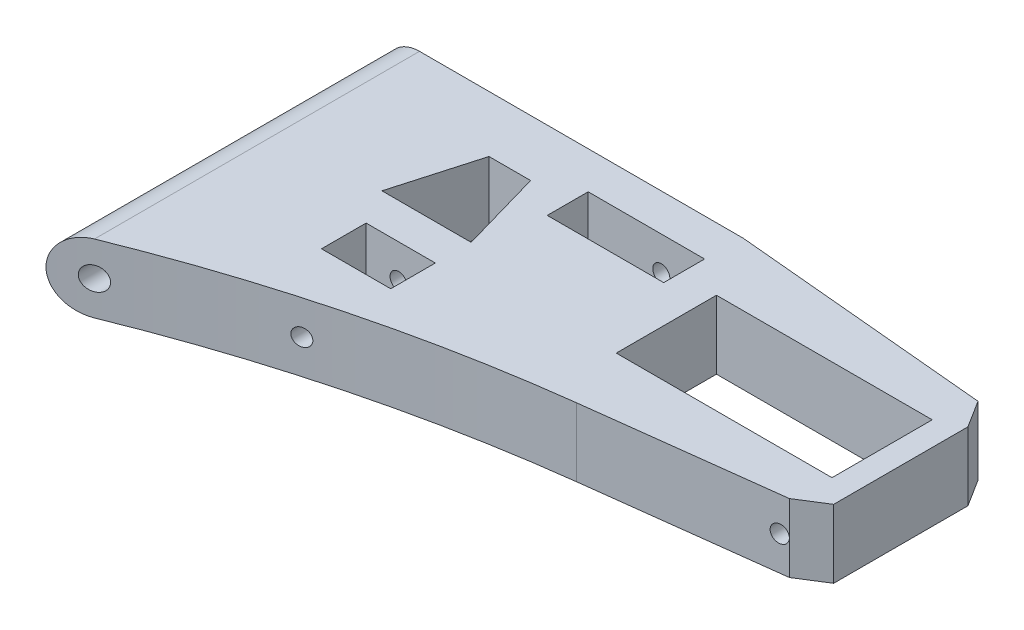
SolidWorks part; units mm, degrees
ref_plane "Front Plane" through (0, 0, 0) normal (0, 0, 1) x (1, 0, 0)
ref_plane "Top Plane" through (0, 0, 0) normal (0, 1, 0) x (1, 0, 0)
ref_plane "Right Plane" through (0, 0, 0) normal (1, 0, 0) x (0, 0, -1)
sketch "Sketch1" plane through (0, 0, 0) normal (0, 1, 0) x (1, 0, 0)
  line L0 (0, 58.1849) -> (0, -59.0181) construction
  line L1 (-25.4, 37.2319) -> (-67.6656, 37.2319)
  line L2 (-67.6656, 37.2319) -> (-86.5378, 37.2319)
  line L3 (-86.5378, 37.2319) -> (-130.7049, 33.1679)
  line L4 (-130.7049, 33.1679) -> (-133.6294, 28.5232)
  line L5 (-133.6294, 28.5232) -> (-133.6294, 5.587)
  line L6 (-133.6294, 5.587) -> (-128.9847, 2.6625)
  line L7 (-128.9847, 2.6625) -> (-96.6642, -1.3466)
  line L8 (-25.4, -20.7309) -> (-25.4, 37.2319)
  line L9 (-63.9064, -0.3535) -> (-65.5989, -7.1304) construction
  line L10 (-129.54, 26.5131) -> (-92.6846, 26.5131)
  line L11 (-129.54, 26.5131) -> (-129.54, 9.3935)
  line L12 (-129.54, 9.3935) -> (-92.6846, 9.3935)
  line L13 (-92.6846, 26.5131) -> (-92.6846, 9.3935)
  line L14 (-86.3119, 30.8565) -> (-66.4237, 30.8565)
  line L15 (-86.3119, 30.8565) -> (-86.3119, 23.8715)
  line L16 (-86.3119, 23.8715) -> (-66.4237, 23.8715)
  line L17 (-66.4237, 30.8565) -> (-66.4237, 23.8715)
  line L18 (-63.9064, 7.2665) -> (-52.0827, 7.2665)
  line L19 (-63.9064, 7.2665) -> (-63.9064, -0.3535)
  line L20 (-63.9064, -0.3535) -> (-52.0827, -0.3535)
  line L21 (-52.0827, 7.2665) -> (-52.0827, -0.3535)
  line L22 (-80.2159, -3.4799) -> (-46.128, -11.9931) construction
  line L23 (-63.9064, 13.3847) -> (-48.6664, 13.3847)
  line L24 (-48.6664, 13.3847) -> (-52.7304, 27.6087)
  line L25 (-52.7304, 27.6087) -> (-59.8424, 27.6087)
  line L26 (-59.8424, 27.6087) -> (-63.9064, 13.3847)
  line L27 (-56.2864, 27.6087) -> (-56.2864, 13.3847) construction
  line L28 (56.2864, 27.6087) -> (56.2864, 13.3847) construction
  line L29 (80.2159, -3.4799) -> (46.128, -11.9931) construction
  line L30 (63.9064, -0.3535) -> (65.5989, -7.1304) construction
  line L31 (59.8424, 27.6087) -> (63.9064, 13.3847)
  line L32 (52.7304, 27.6087) -> (59.8424, 27.6087)
  line L33 (48.6664, 13.3847) -> (52.7304, 27.6087)
  line L34 (63.9064, 13.3847) -> (48.6664, 13.3847)
  line L35 (52.0827, 7.2665) -> (52.0827, -0.3535)
  line L36 (63.9064, -0.3535) -> (52.0827, -0.3535)
  line L37 (63.9064, 7.2665) -> (63.9064, -0.3535)
  line L38 (63.9064, 7.2665) -> (52.0827, 7.2665)
  line L39 (66.4237, 30.8565) -> (66.4237, 23.8715)
  line L40 (86.3119, 23.8715) -> (66.4237, 23.8715)
  line L41 (86.3119, 30.8565) -> (86.3119, 23.8715)
  line L42 (86.3119, 30.8565) -> (66.4237, 30.8565)
  line L43 (92.6846, 26.5131) -> (92.6846, 9.3935)
  line L44 (129.54, 9.3935) -> (92.6846, 9.3935)
  line L45 (129.54, 26.5131) -> (129.54, 9.3935)
  line L46 (129.54, 26.5131) -> (92.6846, 26.5131)
  line L47 (25.4, -20.7309) -> (25.4, 37.2319)
  line L48 (128.9847, 2.6625) -> (96.6642, -1.3466)
  line L49 (133.6294, 5.587) -> (128.9847, 2.6625)
  line L50 (133.6294, 28.5232) -> (133.6294, 5.587)
  line L51 (130.7049, 33.1679) -> (133.6294, 28.5232)
  line L52 (86.5378, 37.2319) -> (130.7049, 33.1679)
  line L53 (67.6656, 37.2319) -> (86.5378, 37.2319)
  line L54 (25.4, 37.2319) -> (67.6656, 37.2319)
  arc A0 (-96.6642, -1.3466) -> (-25.4, -20.7309) centre (-128.7454, -259.9793) cw
  arc A1 (96.6642, -1.3466) -> (25.4, -20.7309) centre (128.7454, -259.9793) ccw
  dimension "D1" = 57.9628
  dimension "D2" = 108.2294
  dimension "D3" = 22.9362
  dimension "D4" = 30.5054
  dimension "D5" = 4.0894
  dimension "D6" = 6.6548
  dimension "D7" = 17.1196
  dimension "D8" = 36.8554
  dimension "D9" = 47.0916
  dimension "D10" = 6.3754
  dimension "D11" = 19.8882
  dimension "D12" = 6.985
  dimension "D13" = 11.8237
  dimension "D14" = 7.62
  dimension "D15" = 69.723
  dimension "D16" = 25.4
  dimension "D17" = 6.985
  dimension "D18" = 4.064
  dimension "D19" = 18.8722
  dimension "D20" = 7.112
  dimension "D21" = 15.24
  dimension "D22" = 14.224
extrude "Boss-Extrude1" add sketch "Sketch1" along normal blind 11.684
sketch "Sketch2" plane through (0, 0, 0) normal (0, 0, 1) x (1, 0, 0)
  line L0 (0, 33.0453) -> (0, -31.8853) construction
  line L1 (57.7926, 5.842) -> (-46.4651, 5.842) construction
  line L6 (-25.4, 11.684) -> (-96.6642, 11.684) construction
  line L7 (-96.6642, 0) -> (-25.4, 0) construction
  line L8 (-25.4, 11.684) -> (-25.4, 0) construction
  line L9 (-31.242, 11.684) -> (-25.4, 11.684)
  line L10 (-25.4, 11.684) -> (-25.4, 5.842)
  line L11 (-31.242, 0) -> (-25.4, 0)
  line L12 (-25.4, 0) -> (-25.4, 5.842)
  line L13 (25.4, 0) -> (25.4, 5.842)
  line L14 (31.242, 0) -> (25.4, 0)
  line L15 (25.4, 11.684) -> (25.4, 5.842)
  line L16 (31.242, 11.684) -> (25.4, 11.684)
  arc A0 (-31.242, 11.684) -> (-31.242, 0) centre (-31.242, 5.842) cw
  arc A1 (31.242, 11.684) -> (31.242, 0) centre (31.242, 5.842) ccw
sketch "Sketch3" plane through (0, 0, 0) normal (0, 0, 1) x (1, 0, 0)
  line L0 (-127.5242, 11.684) -> (-127.5242, 0) construction
  line L1 (-128.9847, 11.684) -> (-96.6642, 11.684) construction
  line L2 (-128.9847, 0) -> (-96.6642, 0) construction
  line L3 (-128.9847, 11.684) -> (-128.9847, 0) construction
  line L4 (0, 26.0336) -> (0, -23.8731) construction
  line L5 (127.5242, 11.684) -> (127.5242, 0) construction
  circle A0 centre (-127.5242, 5.842) radius 1.4605
  circle A1 centre (127.5242, 5.842) radius 1.4605
  dimension "D1" = 2.921
extrude "Cut-Extrude8" cut sketch "Sketch3" against normal through all
sketch "Sketch4" plane through (0, 0, -37.2319) normal (0, 0, -1) x (-1, 0, 0)
  line L0 (78.9178, 11.684) -> (78.9178, 0) construction
  line L1 (25.4, 11.684) -> (86.5378, 11.684) construction
  line L2 (25.4, 0) -> (86.5378, 0) construction
  line L3 (86.5378, 11.684) -> (86.5378, 0) construction
  line L4 (0, -10.6452) -> (0, 23.3535) construction
  line L5 (-78.9178, 11.684) -> (-78.9178, 0) construction
  circle A0 centre (78.9178, 5.842) radius 1.4605
  circle A1 centre (-78.9178, 5.842) radius 1.4605
  dimension "D2" = 2.921
  dimension "D1" = 7.62
extrude "Cut-Extrude9" cut sketch "Sketch4" against normal blind 18.034
extrude "Cut-Extrude11" cut sketch "Sketch2" against normal mid plane 76.2 contours A1 L13 L14 | A1 L16 L15
delete or keep bodies "Body-Delete/Keep 1" type delete bodies bodies 107
sketch "Sketch6" plane through (0, 0, 0) normal (0, 0, 1) x (1, 0, 0)
  line L0 (57.6326, 11.684) -> (57.6326, 0) construction
  line L1 (96.6642, 11.684) -> (31.242, 11.684) construction
  line L2 (31.242, 0) -> (96.6642, 0) construction
  arc A0 (31.242, 11.684) -> (31.242, 0) centre (31.242, 5.842) ccw construction
  circle A1 centre (57.6326, 5.842) radius 1.4605
  dimension "D1" = 26.3906
  dimension "D2" = 2.921
extrude "Cut-Extrude12" cut sketch "Sketch6" against normal mid plane 32.639
sketch "Sketch7" plane through (0, 0, 0) normal (0, 0, 1) x (1, 0, 0)
  line L0 (31.242, 11.684) -> (31.242, 0) construction
  line L1 (96.6642, 11.684) -> (31.242, 11.684) construction
  line L2 (31.242, 0) -> (96.6642, 0) construction
  circle A0 centre (31.242, 5.842) radius 1.9685
  arc A1 (31.242, 11.684) -> (31.242, 0) centre (31.242, 5.842) ccw construction
  dimension "D1" = 3.937
extrude "Cut-Extrude13" cut sketch "Sketch7" against normal through all both and the other way through all
sketch "Sketch8" plane through (0, 0, 0) normal (0, -1, 0) x (1, 0, 0)
  line L0 (25.4, 20.7309) -> (25.4, -37.2319) construction
  line L1 (34.8709, 3.534) -> (24.2189, 9.0852)
  line L2 (33.6315, -9.9251) -> (24.6584, -12.6691)
  line L3 (24.6584, -12.6691) -> (24.2189, 9.0852)
  arc A0 (33.6315, -9.9251) -> (34.8709, 3.534) centre (31.496, -2.9419) ccw
  dimension "D3" = 14.605
  dimension "D1" = 23.6728
  dimension "D2" = 6.096
extrude "Cut-Extrude14" cut sketch "Sketch8" against normal blind 7.62
